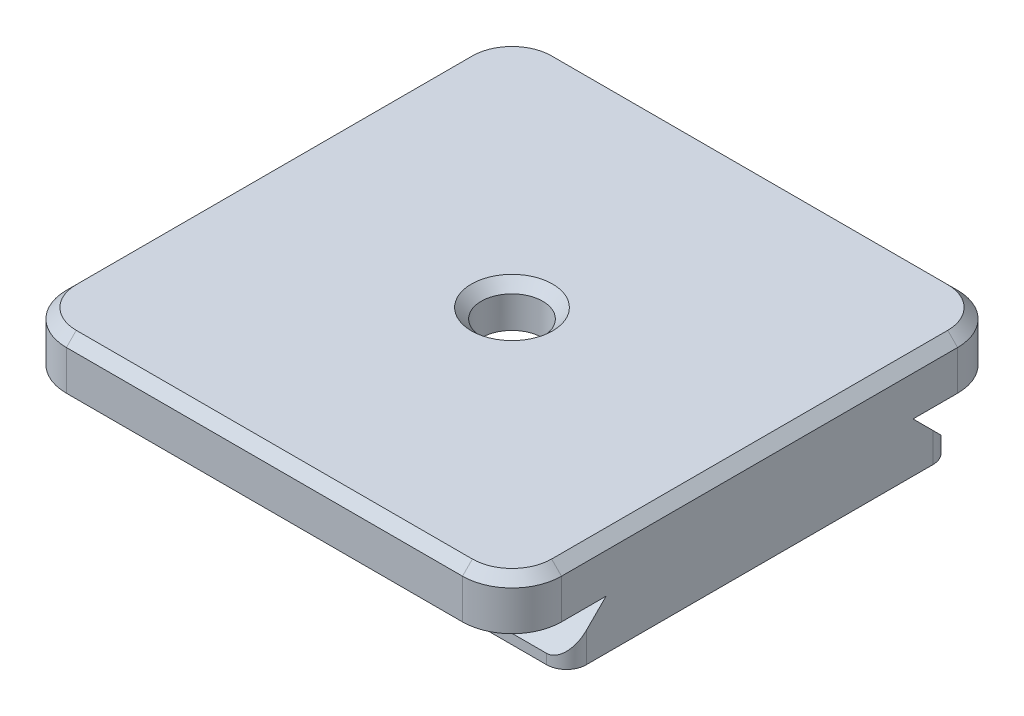
SolidWorks part; units mm, degrees
ref_plane "Front Plane" through (0, 0, 0) normal (0, 0, 1) x (1, 0, 0)
ref_plane "Top Plane" through (0, 0, 0) normal (0, 1, 0) x (1, 0, 0)
ref_plane "Right Plane" through (0, 0, 0) normal (1, 0, 0) x (0, 0, -1)
sketch "Sketch1" plane through (0, 0, 0) normal (0, 1, 0) x (1, 0, 0)
  line L1 (25, -25) -> (-25, -25)
  line L2 (25, -25) -> (25, 25)
  line L3 (25, 25) -> (-25, 25)
  line L4 (-25, -25) -> (-25, 25)
  line L5 (25, -25) -> (-25, 25) construction
  line L6 (25, 25) -> (-25, -25) construction
  point P0 (0, 0)
  dimension "D1" = 50
  dimension "D2" = 50
extrude "Boss-Extrude1" add sketch "Sketch1" along normal blind 10
sketch "Sketch4" plane through (0, 0, 0) normal (0, -1, 0) x (-1, 0, 0)
  line L0 (21, -7.2284) -> (21, -10.5)
  line L1 (-18.5, 13) -> (18.5, 13)
  line L2 (-21, 10.5) -> (-21, 7.2284)
  line L3 (-18.5, -13) -> (18.5, -13)
  line L4 (21, 10.5) -> (21, 7.2284)
  line L5 (-21, 13) -> (21, -13) construction
  line L6 (-21, -13) -> (21, 13) construction
  line L7 (-21, -7.2284) -> (-21, -10.5)
  arc A0 (19.5333, 5.3008) -> (19.5333, -5.3008) centre (21, 0) ccw
  arc A1 (-19.5333, -5.3008) -> (-19.5333, 5.3008) centre (-21, 0) ccw
  arc A2 (-21, -10.5) -> (-18.5, -13) centre (-18.5, -10.5) ccw
  arc A3 (-18.5, 13) -> (-21, 10.5) centre (-18.5, 10.5) ccw
  arc A4 (18.5, 13) -> (21, 10.5) centre (18.5, 10.5) cw
  arc A5 (18.5, -13) -> (21, -10.5) centre (18.5, -10.5) ccw
  arc A6 (-19.5333, -5.3008) -> (-21, -7.2284) centre (-19, -7.2284) ccw
  arc A7 (-21, 7.2284) -> (-19.5333, 5.3008) centre (-19, 7.2284) ccw
  arc A8 (19.5333, 5.3008) -> (21, 7.2284) centre (19, 7.2284) ccw
  arc A9 (19.5333, -5.3008) -> (21, -7.2284) centre (19, -7.2284) cw
  point P0 (0, 0)
  point P26 (-21, -5.5)
  point P33 (21, -5.5)
  dimension "D3" = 11
  dimension "D4" = 11
  dimension "D5" = 2.5
  dimension "D6" = 2
  dimension "D1" = 42
  dimension "D2" = 26
extrude "Cut-Extrude3" cut sketch "Sketch4" against normal blind 6.3
sketch "Sketch5" plane through (0, 6.3, 0) normal (0, -1, 0) x (-1, 0, 0)
  circle A0 centre (0, 0) radius 6.5
  circle A1 centre (0, 0) radius 3.1
  dimension "D1" = 13
  dimension "D2" = 6.2
extrude "Boss-Extrude2" add sketch "Sketch5" along normal blind 0.5
sketch "Sketch6" plane through (0, 0, 0) normal (0, -1, 0) x (1, 0, 0)
  line L0 (-25, -25) -> (-25, 25) construction
  circle A0 centre (-20, 0) radius 2.7
  circle A1 centre (20, 0) radius 2.7
  dimension "D1" = 5.4
  dimension "D2" = 40
  dimension "D3" = 5
extrude "Boss-Extrude3" add sketch "Sketch6" along normal blind 2.5
fillet "Fillet1" radius 0.5 2 edges at (20, -2.5, -2.7) (-20, -2.5, -2.7)
sketch "Sketch8" plane through (25, 0, 0) normal (1, 0, 0) x (0, 0, -1)
  line L0 (25, 10) -> (25, 0) construction
  line L16 (-25, 0) -> (-25, 5)
  line L17 (-25, 5) -> (-15.5, 5)
  line L18 (25, 0) -> (25, 5)
  line L19 (15.5, 5) -> (25, 5)
  line L20 (-25, 0) -> (25, 0) construction
  line L22 (-20.5, 0) -> (-15.5, 5)
  line L23 (20.5, 0) -> (15.5, 5)
  line L24 (-20.5, 0) -> (-25, 0)
  line L25 (20.5, 0) -> (25, 0)
  dimension "D1" = 9.5
  dimension "D2" = 45
extrude "Cut-Extrude4" cut sketch "Sketch8" against normal through all
fillet "Fillet2" radius 5 4 edges at (25, 7.5, -25) (-25, 7.5, -25) (-25, 7.5, 25) (25, 7.5, 25)
chamfer "Chamfer1" distance 1 angle 45 8 edges at (23.5355, 10, 23.5355) (0, 10, 25) (-23.5355, 10, 23.5355) (-25, 10, 0) (-23.5355, 10, -23.5355) (0, 10, -25) (23.5355, 10, -23.5355) (25, 10, 0)
chamfer "Chamfer2" distance 1 angle 90 2 edges at (0, 0, 20.5) (0, 0, -20.5)
fillet "Fillet3" radius 2 4 edges at (25, 0.5, -19.5) (25, 0.5, 19.5) (-25, 0.5, 19.5) (-25, 0.5, -19.5)
sketch "Sketch9" plane through (0, 6.3, 0) normal (0, -1, 0) x (-1, 0, 0)
  circle A0 centre (0, 0) radius 3.1
extrude "Cut-Extrude5" cut sketch "Sketch9" against normal through all
chamfer "Chamfer3" distance 1 angle 45 1 edges at (0, 10, -3.1)
